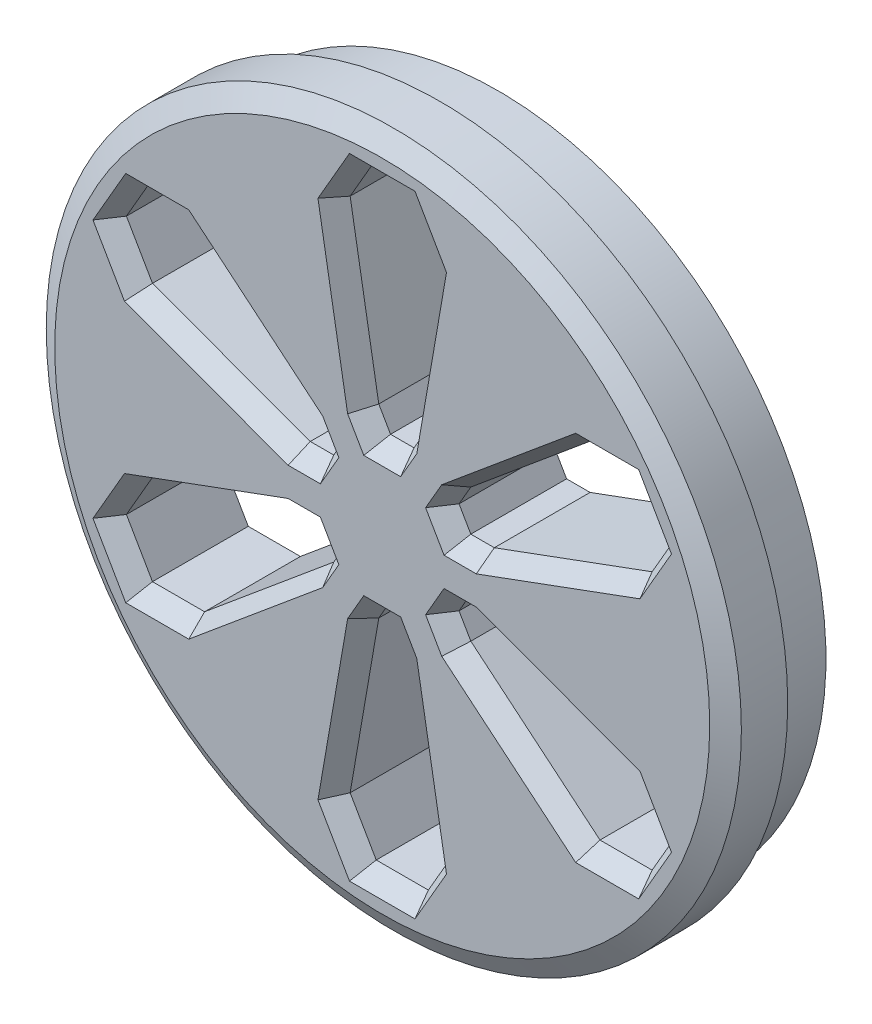
SolidWorks part; units mm, degrees
ref_plane "정면" through (0, 0, 0) normal (0, 0, 1) x (1, 0, 0)
ref_plane "윗면" through (0, 0, 0) normal (0, 1, 0) x (1, 0, 0)
ref_plane "우측면" through (0, 0, 0) normal (1, 0, 0) x (0, 0, -1)
sketch "스케치1" plane through (0, 0, 0) normal (0, 0, 1) x (1, 0, 0)
  line L0 (4.5, 22.3) -> (2.0296, 8)
  line L1 (-2.0296, 8) -> (-4.5, 22.3)
  line L2 (23.8124, 11.15) -> (21.5624, 15.0471)
  line L3 (4.5, 22.3) -> (2.25, 26.1971)
  line L4 (2.25, 26.1971) -> (-2.25, 26.1971)
  line L5 (-2.25, 26.1971) -> (-4.5, 22.3)
  line L6 (21.5624, 15.0471) -> (17.0624, 15.0471)
  line L7 (21.5624, 7.2529) -> (23.8124, 11.15)
  line L8 (21.5624, 7.2529) -> (7.943, 2.2423)
  line L9 (-2.25, 18.4029) -> (0, 18.4029) [skipped]
  line L10 (-4.5, 22.3) -> (-4.2626, 21.8888) [skipped]
  line L11 (4.2626, 21.8888) -> (4.5, 22.3) [skipped]
  line L12 (-2.0296, 8) -> (-1.0148, 6.2423)
  line L13 (-1.0148, 6.2423) -> (1.0148, 6.2423)
  line L14 (1.0148, 6.2423) -> (2.0296, 8)
  line L15 (0, 9.7577) -> (-1.0148, 9.7577) [skipped]
  line L16 (-1.5222, 8.8789) -> (-2.0296, 8) [skipped]
  line L17 (2.0296, 8) -> (1.5222, 8.8789) [skipped]
  line L18 (5.9134, 5.7577) -> (17.0624, 15.0471)
  line L19 (5.9134, 2.2423) -> (7.943, 2.2423)
  line L20 (4.8986, 4) -> (5.9134, 2.2423)
  line L21 (5.9134, 5.7577) -> (4.8986, 4)
  line L22 (21.5624, -15.0471) -> (23.8124, -11.15)
  line L23 (23.8124, -11.15) -> (21.5624, -7.2529)
  line L24 (17.0624, -15.0471) -> (21.5624, -15.0471)
  line L25 (17.0624, -15.0471) -> (5.9134, -5.7577)
  line L26 (7.943, -2.2423) -> (21.5624, -7.2529)
  line L27 (4.8986, -4) -> (5.9134, -5.7577)
  line L28 (5.9134, -2.2423) -> (4.8986, -4)
  line L29 (7.943, -2.2423) -> (5.9134, -2.2423)
  line L30 (-2.25, -26.1971) -> (2.25, -26.1971)
  line L31 (2.25, -26.1971) -> (4.5, -22.3)
  line L32 (-4.5, -22.3) -> (-2.25, -26.1971)
  line L33 (-4.5, -22.3) -> (-2.0296, -8)
  line L34 (2.0296, -8) -> (4.5, -22.3)
  line L35 (-1.0148, -6.2423) -> (-2.0296, -8)
  line L36 (1.0148, -6.2423) -> (-1.0148, -6.2423)
  line L37 (2.0296, -8) -> (1.0148, -6.2423)
  line L38 (-23.8124, -11.15) -> (-21.5624, -15.0471)
  line L39 (-21.5624, -15.0471) -> (-17.0624, -15.0471)
  line L40 (-21.5624, -7.2529) -> (-23.8124, -11.15)
  line L41 (-21.5624, -7.2529) -> (-7.943, -2.2423)
  line L42 (-5.9134, -5.7577) -> (-17.0624, -15.0471)
  line L43 (-5.9134, -2.2423) -> (-7.943, -2.2423)
  line L44 (-4.8986, -4) -> (-5.9134, -2.2423)
  line L45 (-5.9134, -5.7577) -> (-4.8986, -4)
  line L46 (-21.5624, 15.0471) -> (-23.8124, 11.15)
  line L47 (-23.8124, 11.15) -> (-21.5624, 7.2529)
  line L48 (-17.0624, 15.0471) -> (-21.5624, 15.0471)
  line L49 (-17.0624, 15.0471) -> (-5.9134, 5.7577)
  line L50 (-7.943, 2.2423) -> (-21.5624, 7.2529)
  line L51 (-4.8986, 4) -> (-5.9134, 5.7577)
  line L52 (-5.9134, 2.2423) -> (-4.8986, 4)
  line L53 (-7.943, 2.2423) -> (-5.9134, 2.2423)
  circle A0 centre (0, 0) radius 30
  circle A1 centre (0, 0) radius 24 construction
  point P55 (0, 0)
  point P56 (0, 0)
  dimension "D1" = 60
  dimension "D3" = 6
  dimension "D2" = 6
extrude "보스-돌출1" add sketch "스케치1" along normal blind 10
sketch "스케치3" plane through (0, 0, 0) normal (0, 0, -1) x (-1, 0, 0)
  circle A0 centre (0, 0) radius 4.0642
extrude "컷-돌출1" cut sketch "스케치3" against normal blind 7
sketch "스케치4" plane through (0, 0, 0) normal (0, 0, -1) x (-1, 0, 0)
  circle A0 centre (0, 0) radius 28.3
  dimension "D1" = 56.6
extrude "컷-돌출2" cut sketch "스케치4" against normal blind 5 flip side to cut
chamfer "모따기2" distance 1 angle 60 49 edges at (30, 0, 10) (-5.406, 3.1211, 10) (-5.406, 4.8789, 10) (-11.4879, 10.4024, 10) (-19.3124, 15.0471, 10) (-22.6874, 13.0986, 10) (-22.6874, 9.2014, 10) (-14.7527, 4.7476, 10) (-6.9282, 2.2423, 10) (-5.406, -3.1211, 10) (-6.9282, -2.2423, 10) (-14.7527, -4.7476, 10) (-22.6874, -9.2014, 10) (-22.6874, -13.0986, 10) (-19.3124, -15.0471, 10) (-11.4879, -10.4024, 10) (-5.406, -4.8789, 10) (0, -6.2423, 10) (-1.5222, -7.1211, 10) (-3.2648, -15.15, 10) (-3.375, -24.2486, 10) (0, -26.1971, 10) (3.375, -24.2486, 10) (3.2648, -15.15, 10) (1.5222, -7.1211, 10) (5.406, -3.1211, 10) (5.406, -4.8789, 10) (11.4879, -10.4024, 10) (19.3124, -15.0471, 10) (22.6874, -13.0986, 10) (22.6874, -9.2014, 10) (14.7527, -4.7476, 10) (6.9282, -2.2423, 10) (5.406, 3.1211, 10) (6.9282, 2.2423, 10) (14.7527, 4.7476, 10) (22.6874, 9.2014, 10) (22.6874, 13.0986, 10) (19.3124, 15.0471, 10) (11.4879, 10.4024, 10) (5.406, 4.8789, 10) (3.2648, 15.15, 10) (3.375, 24.2486, 10) (0, 26.1971, 10) (-3.375, 24.2486, 10) (-3.2648, 15.15, 10) (-1.5222, 7.1211, 10) (0, 6.2423, 10) (1.5222, 7.1211, 10)
